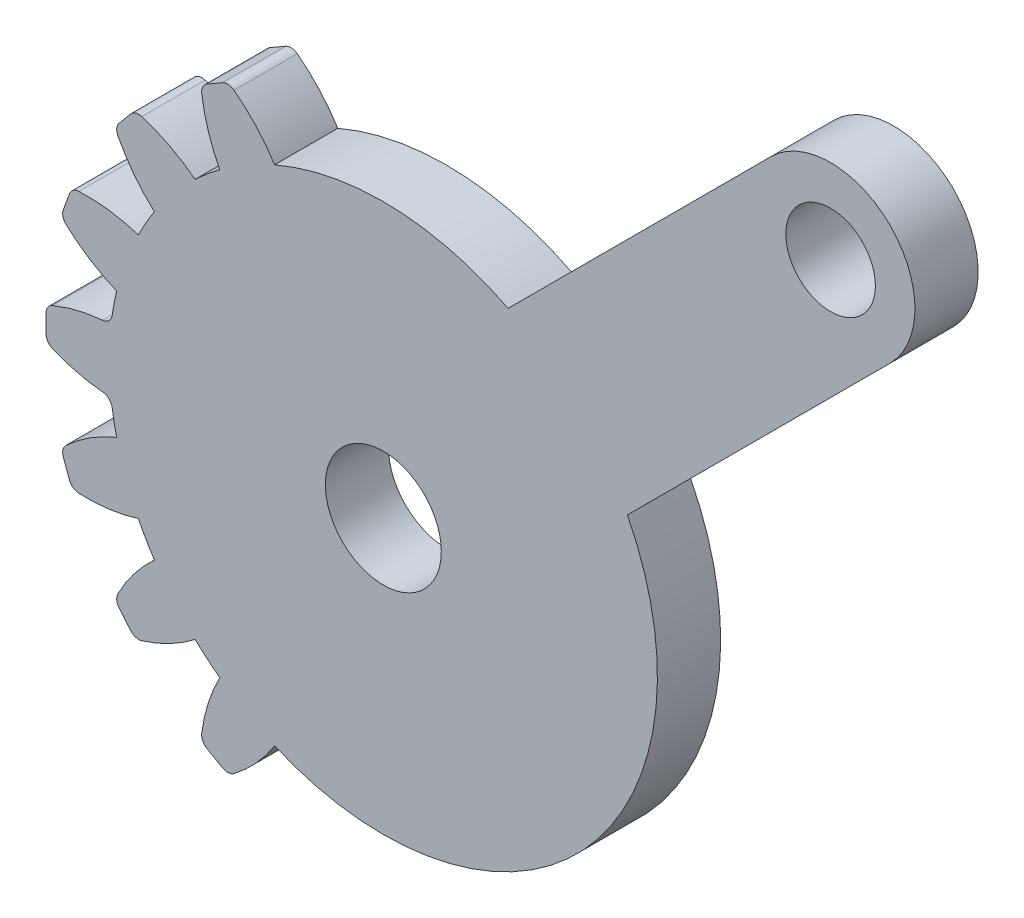
SolidWorks part; units mm, degrees
material "ABS"
ref_plane "Front Plane" through (0, 0, 0) normal (0, 0, 1) x (1, 0, 0)
ref_plane "Top Plane" through (0, 0, 0) normal (0, 1, 0) x (1, 0, 0)
ref_plane "Right Plane" through (0, 0, 0) normal (1, 0, 0) x (0, 0, -1)
sketch "Sketch1" plane through (0, 0, 0) normal (0, 0, 1) x (1, 0, 0)
  circle A1 centre (43.95, -5.65) radius 2.75
  circle A2 centre (43.95, -5.65) radius 13
  dimension "D1" = 26
  dimension "D2" = 5.5
extrude "Boss-Extrude1" add sketch "Sketch1" along normal blind 3 contours A2
sketch "Sketch2" plane through (0, 0, 3) normal (0, 0, 1) x (1, 0, 0)
  line L0 (43.95, -5.65) -> (-22.5318, -5.65) construction
  line L1 (27.95, -4.9) -> (27.95, -6.4)
  arc A0 (27.95, -6.4) -> (31.0368, -7.15) centre (31.3446, 0.8441) ccw
  arc A1 (31.0368, -4.15) -> (31.0368, -7.15) centre (43.95, -5.65) ccw
  circle A2 centre (43.95, -5.65) radius 13 construction
  arc A3 (27.95, -4.9) -> (31.0368, -4.15) centre (31.3446, -12.1441) cw
  point P10 (27.95, -5.65)
  dimension "D3" = 8
  dimension "D1" = 0.75
  dimension "D2" = 1.5
  dimension "D4" = 16
extrude "Boss-Extrude2" add sketch "Sketch2" against normal blind 3
fillet "Fillet1" radius 0.5 4 edges at (31.0368, -7.15, 1.5) (27.95, -6.4, 1.5) (27.95, -4.9, 1.5) (31.0368, -4.15, 1.5)
pattern_circular "CirPattern1" count 4 over 60 about axis through (43.95, -5.65, 0) along (0, 0, 1) of "Boss-Extrude2"
pattern_circular "CirPattern2" count 4 over 60 about axis through (43.95, -5.65, 0) along (0, 0, 1) of "Boss-Extrude2"
sketch "Sketch3" plane through (0, 0, 3) normal (0, 0, 1) x (1, 0, 0)
  line L0 (43.95, -5.65) -> (75.3027, -5.65) construction
  line L1 (44.4697, 0.5266) -> (62.3348, 18.3916)
  line L2 (67.9916, 12.7348) -> (50.5183, -4.7385)
  line L3 (65.1632, 15.5632) -> (43.95, -5.65) construction
  line L4 (44.4697, 0.5266) -> (50.5183, -4.7385)
  arc A0 (62.3348, 18.3916) -> (67.9916, 12.7348) centre (65.1632, 15.5632) cw
  circle A1 centre (65.1632, 15.5632) radius 2.125
  dimension "D4" = 4.25
  dimension "D1" = 8
  dimension "D2" = 30
  dimension "D3" = 45
  dimension "D5" = 5
extrude "Boss-Extrude3" add sketch "Sketch3" against normal blind 3
fillet "Fillet2" radius 0.5 12 edges at (36.5995, -19.8814, 1.5) (35.3005, -19.1314, 1.5) (32.1754, -16.5091, 1.5) (31.2112, -15.3601, 1.5) (29.1714, -11.8271, 1.5) (28.6584, -10.4176, 1.5) (28.6584, -0.8824, 1.5) (29.1714, 0.5271, 1.5) (31.2112, 4.0601, 1.5) (32.1754, 5.2091, 1.5) (36.5995, 8.5814, 1.5) (35.3005, 7.8314, 1.5)
